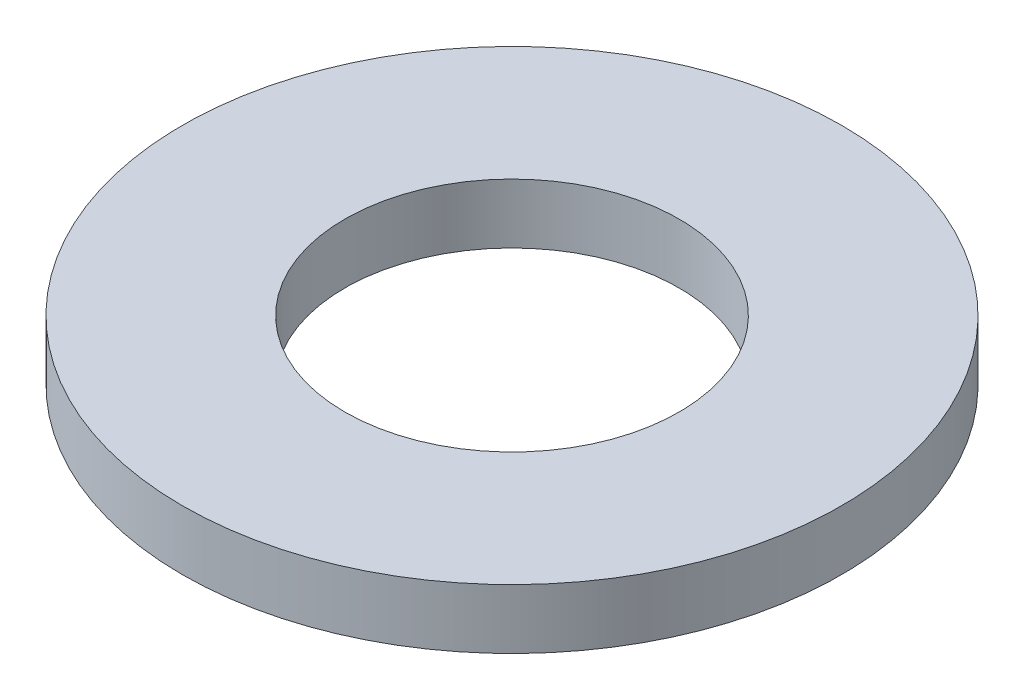
SolidWorks part; units mm, degrees
ref_plane "Front"
ref_plane "Top" through (0, 0, 0) normal (0, 1, 0) x (1, 0, 0)
ref_plane "Right" through (0, 0, 0) normal (1, 0, 0) x (0, 0, -1)
sketch "Sketch1" plane through (0, 0, 0) normal (0, 1, 0) x (1, 0, 0)
  circle A0 centre (0, 0) radius 4.445
  circle A1 centre (0, 0) radius 8.763
  dimension "D1" = 8.89
  dimension "D2" = 17.526
extrude "Extrude1" add sketch "Sketch1" along normal blind 1.5875
